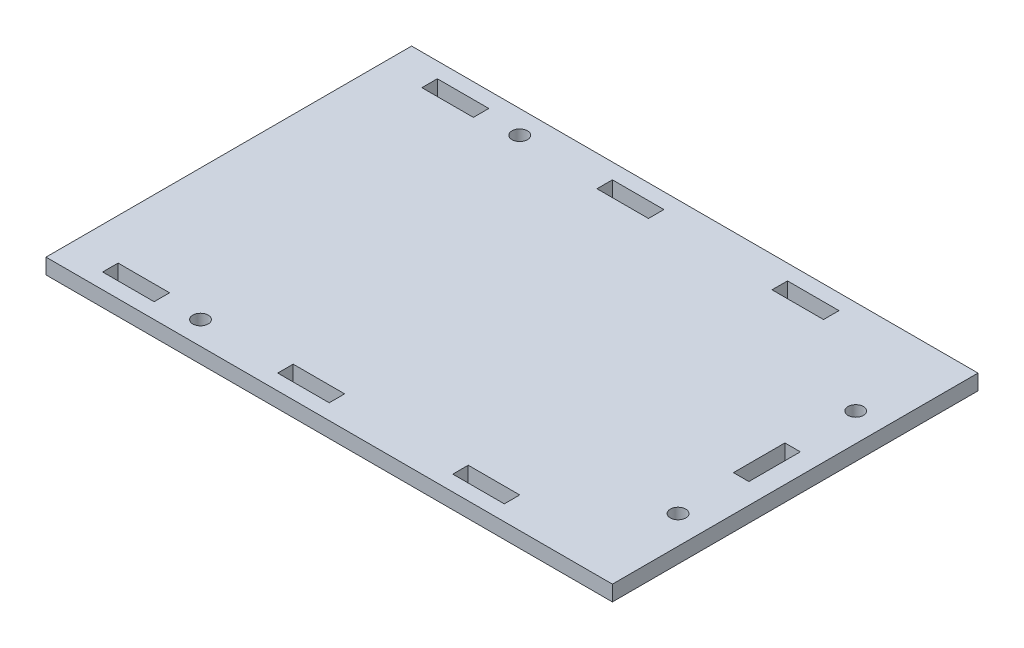
SolidWorks part; units mm, degrees
ref_plane "Front Plane" through (0, 0, 0) normal (0, 0, 1) x (1, 0, 0)
ref_plane "Top Plane" through (0, 0, 0) normal (0, 1, 0) x (1, 0, 0)
ref_plane "Right Plane" through (0, 0, 0) normal (1, 0, 0) x (0, 0, -1)
sketch "Sketch1" plane through (0, 0, 0) normal (0, 1, 0) x (1, 0, 0)
  line L0 (-4, 35.5) -> (-110, 35.5) construction
  line L1 (0, 0) -> (-110, 0)
  line L2 (0, 0) -> (0, 71)
  line L3 (0, 71) -> (-110, 71)
  line L4 (-110, 0) -> (-110, 71)
  line L9 (-68, 6) -> (-58, 6)
  line L10 (-4, 30.5) -> (-4, 40.5)
  line L11 (-4, 40.5) -> (-7, 40.5)
  line L12 (-7, 40.5) -> (-7, 30.5)
  line L13 (-7, 30.5) -> (-4, 30.5)
  line L14 (-24, 3) -> (-34, 3)
  line L15 (-34, 3) -> (-34, 6)
  line L16 (-34, 6) -> (-24, 6)
  line L17 (-24, 6) -> (-24, 3)
  line L18 (-58, 6) -> (-58, 3)
  line L19 (-58, 3) -> (-68, 3)
  line L20 (-68, 3) -> (-68, 6)
  line L21 (-102, 6) -> (-92, 6)
  line L22 (-92, 6) -> (-92, 3)
  line L23 (-92, 3) -> (-102, 3)
  line L24 (-102, 3) -> (-102, 6)
  line L25 (-24, 68) -> (-34, 68)
  line L26 (-24, 65) -> (-24, 68)
  line L27 (-34, 65) -> (-24, 65)
  line L28 (-34, 68) -> (-34, 65)
  line L29 (-58, 68) -> (-68, 68)
  line L30 (-58, 65) -> (-58, 68)
  line L31 (-68, 65) -> (-58, 65)
  line L32 (-68, 68) -> (-68, 65)
  line L33 (-102, 68) -> (-102, 65)
  line L34 (-102, 65) -> (-92, 65)
  line L35 (-92, 65) -> (-92, 68)
  line L36 (-92, 68) -> (-102, 68)
  circle A1 centre (-5.5, 18.25) radius 1.5
  circle A2 centre (-5.5, 52.75) radius 1.5
  circle A3 centre (-84.5, 4.5) radius 1.5
  circle A4 centre (-84.5, 66.5) radius 1.5
  point P5 (-5.5, 30.5)
  point P30 (-92, 4.5)
  point P31 (0, 0)
  dimension "D7" = 3
  dimension "D4" = 3
  dimension "D13" = 3
  dimension "D1" = 110
  dimension "D2" = 71
  dimension "D3" = 18.25
  dimension "D5" = 5.5
  dimension "D6" = 10
  dimension "D8" = 12.25
  dimension "D9" = 24
  dimension "D10" = 3
  dimension "D12" = 24
  dimension "D14" = 7.5
  dimension "D11" = 3
extrude "Boss-Extrude1" add sketch "Sketch1" along normal blind 3
